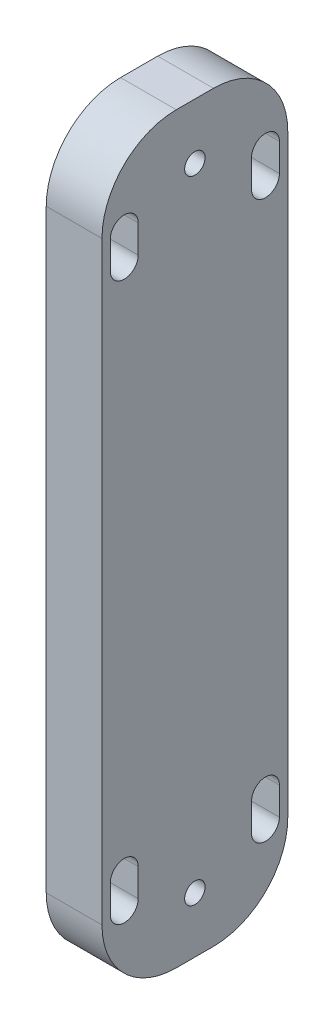
SolidWorks part; units mm, degrees
ref_plane "Спереди" through (0, 0, 0) normal (0, 0, 1) x (1, 0, 0)
ref_plane "Сверху" through (0, 0, 0) normal (0, 1, 0) x (1, 0, 0)
ref_plane "Справа" through (0, 0, 0) normal (1, 0, 0) x (0, 0, -1)
sketch "Эскиз1" plane through (0, 0, 0) normal (1, 0, 0) x (0, 0, -1)
  line L0 (1.2, 35.75) -> (1.2, 34.25) construction
  line L1 (4, 0) -> (6, 0)
  line L2 (0, 4) -> (0, 36)
  line L3 (4, 40) -> (6, 40)
  line L4 (10, 4) -> (10, 36)
  line L5 (1.95, 35.75) -> (1.95, 34.25)
  line L6 (0.45, 35.75) -> (0.45, 34.25)
  line L7 (1.2, 4.25) -> (1.2, 5.75) construction
  line L8 (0.45, 4.25) -> (0.45, 5.75)
  line L9 (1.95, 4.25) -> (1.95, 5.75)
  line L10 (8.8, 4.25) -> (8.8, 5.75) construction
  line L11 (8.05, 4.25) -> (8.05, 5.75)
  line L12 (9.55, 4.25) -> (9.55, 5.75)
  line L13 (8.8, 34.25) -> (8.8, 35.75) construction
  line L14 (8.05, 34.25) -> (8.05, 35.75)
  line L15 (9.55, 34.25) -> (9.55, 35.75)
  arc A0 (6, 40) -> (10, 36) centre (6, 36) cw
  arc A1 (0, 36) -> (4, 40) centre (4, 36) cw
  arc A2 (4, 0) -> (0, 4) centre (4, 4) cw
  arc A3 (6, 0) -> (10, 4) centre (6, 4) ccw
  arc A4 (1.95, 35.75) -> (0.45, 35.75) centre (1.2, 35.75) ccw
  arc A5 (0.45, 34.25) -> (1.95, 34.25) centre (1.2, 34.25) ccw
  arc A6 (0.45, 4.25) -> (1.95, 4.25) centre (1.2, 4.25) ccw
  arc A7 (1.95, 5.75) -> (0.45, 5.75) centre (1.2, 5.75) ccw
  circle A8 centre (5, 3) radius 0.55
  circle A9 centre (5, 37) radius 0.55
  arc A10 (8.05, 4.25) -> (9.55, 4.25) centre (8.8, 4.25) ccw
  arc A11 (9.55, 5.75) -> (8.05, 5.75) centre (8.8, 5.75) ccw
  arc A12 (8.05, 34.25) -> (9.55, 34.25) centre (8.8, 34.25) ccw
  arc A13 (9.55, 35.75) -> (8.05, 35.75) centre (8.8, 35.75) ccw
  point P7 (10, 40)
  point P10 (0, 40)
  point P13 (0, 0)
  point P18 (1.2, 35)
  point P25 (1.2, 5)
  point P36 (8.8, 5)
  point P43 (8.8, 35)
  dimension "D3" = 4
  dimension "D4" = 1.1
  dimension "D5" = 1.1
  dimension "D1" = 40
  dimension "D2" = 10
extrude "Бобышка-Вытянуть1" add sketch "Эскиз1" along normal blind 3
